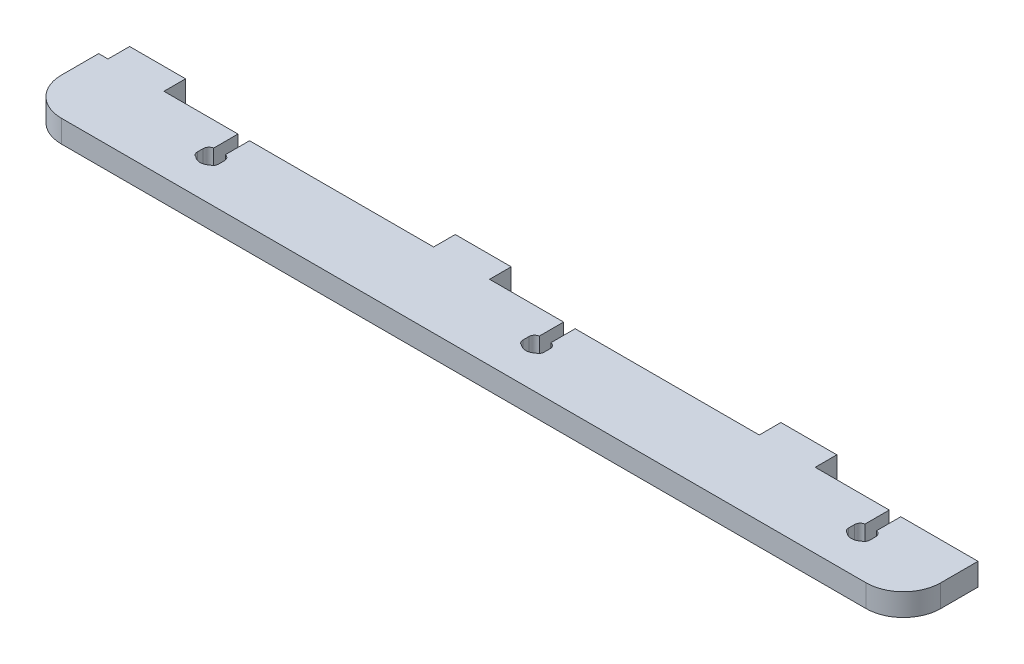
SolidWorks part; units mm, degrees
ref_plane "Alzado" through (0, 0, 0) normal (0, 0, 1) x (1, 0, 0)
ref_plane "Planta" through (0, 0, 0) normal (0, 1, 0) x (1, 0, 0)
ref_plane "Vista lateral" through (0, 0, 0) normal (1, 0, 0) x (0, 0, -1)
sketch "Croquis1" plane through (0, 0, 0) normal (0, 1, 0) x (1, 0, 0)
  line L0 (-32.5, 18.3594) -> (-32.5, 12.5594) construction
  line L1 (193.2444, 12.5594) -> (193.2444, 2.5594)
  line L2 (-42.5, 12.5594) -> (-42.5, 2.5594)
  line L3 (-32.5, -7.4406) -> (183.2444, -7.4406)
  line L7 (-40, 18.3594) -> (-25, 18.3594)
  line L8 (44.8, 12.5594) -> (47.3, 12.5594)
  line L9 (-5.15, 6.0592) -> (-5.15, 12.5594)
  line L10 (-2.05, 6.0592) -> (-2.05, 12.5594)
  line L11 (-0.7597, 4.5311) -> (-0.7597, 2.9811)
  line L12 (-1.4685, 1.6792) -> (-1.6378, 1.6792)
  line L13 (-5.7315, 1.6792) -> (-5.5622, 1.6792)
  line L14 (-6.4403, 4.5311) -> (-6.4403, 2.9811)
  line L15 (132.1, 12.5594) -> (134.6, 12.5594)
  line L16 (82.15, 6.0592) -> (82.15, 12.5594)
  line L17 (169.45, 6.0592) -> (169.45, 12.5594)
  line L18 (172.55, 6.0592) -> (172.55, 12.5594)
  line L19 (173.8403, 4.5311) -> (173.8403, 2.9811)
  line L20 (173.1315, 1.6792) -> (172.9622, 1.6792)
  line L21 (168.8685, 1.6792) -> (169.0378, 1.6792)
  line L22 (168.1597, 4.5311) -> (168.1597, 2.9811)
  line L23 (170.9, 12.5594) -> (170.9, 7.0553) construction
  line L24 (170.9, 12.5594) -> (170.9, 7.0553) construction
  line L25 (-2.05, 12.5594) -> (44.8, 12.5594)
  line L26 (47.3, 18.3594) -> (62.3, 18.3594)
  line L27 (134.6, 18.3594) -> (134.6, 12.5594)
  line L28 (54.8, 18.3594) -> (54.8, 12.5594) construction
  line L29 (35.6211, 12.5594) -> (44.8, 12.5594) construction
  line L30 (85.25, 6.0592) -> (85.25, 12.5594)
  line L31 (86.5403, 4.5311) -> (86.5403, 2.9811)
  line L32 (85.8315, 1.6792) -> (85.6622, 1.6792)
  line L33 (81.5685, 1.6792) -> (81.7378, 1.6792)
  line L34 (80.8597, 4.5311) -> (80.8597, 2.9811)
  line L35 (142.1, 18.3594) -> (142.1, 12.5594) construction
  line L36 (172.55, 12.5594) -> (193.2444, 12.5594)
  line L37 (85.25, 12.5594) -> (132.1, 12.5594)
  line L39 (134.6, 18.3594) -> (149.6, 18.3594)
  line L41 (152.1, 12.5594) -> (169.45, 12.5594)
  line L42 (64.8, 12.5594) -> (82.15, 12.5594)
  line L43 (54.8, 12.5594) -> (55.6211, 12.5594)
  line L44 (54.8, 12.5594) -> (55.6211, 12.5594) construction
  line L45 (-22.5, 12.5594) -> (-5.15, 12.5594)
  line L46 (47.3, 18.3594) -> (47.3, 12.5594)
  line L47 (-22.5, 12.5594) -> (-25, 12.5594)
  line L48 (-25, 18.3594) -> (-25, 12.5594)
  line L51 (-42.5, 12.5594) -> (-40, 12.5594)
  line L52 (-40, 18.3594) -> (-40, 12.5594)
  line L53 (64.8, 12.5594) -> (62.3, 12.5594)
  line L54 (62.3, 18.3594) -> (62.3, 12.5594)
  line L55 (152.1, 12.5594) -> (149.6, 12.5594)
  line L56 (149.6, 18.3594) -> (149.6, 12.5594)
  arc A0 (-0.7597, 4.5311) -> (-2.05, 6.0592) centre (-2.3097, 4.5311) ccw
  arc A1 (-1.4685, 1.6792) -> (-0.7597, 2.9811) centre (-2.3097, 2.9811) ccw
  arc A2 (-5.5622, 1.6792) -> (-1.6378, 1.6792) centre (-3.6, 3.6407) ccw
  arc A3 (-5.7315, 1.6792) -> (-6.4403, 2.9811) centre (-4.8903, 2.9811) cw
  arc A4 (-6.4403, 4.5311) -> (-5.15, 6.0592) centre (-4.8903, 4.5311) cw
  arc A5 (173.8403, 4.5311) -> (172.55, 6.0592) centre (172.2903, 4.5311) ccw
  arc A6 (173.1315, 1.6792) -> (173.8403, 2.9811) centre (172.2903, 2.9811) ccw
  arc A7 (169.0378, 1.6792) -> (172.9622, 1.6792) centre (171, 3.6407) ccw
  arc A8 (168.8685, 1.6792) -> (168.1597, 2.9811) centre (169.7097, 2.9811) cw
  arc A9 (168.1597, 4.5311) -> (169.45, 6.0592) centre (169.7097, 4.5311) cw
  arc A10 (86.5403, 4.5311) -> (85.25, 6.0592) centre (84.9903, 4.5311) ccw
  arc A11 (85.8315, 1.6792) -> (86.5403, 2.9811) centre (84.9903, 2.9811) ccw
  arc A12 (81.7378, 1.6792) -> (85.6622, 1.6792) centre (83.7, 3.6407) ccw
  arc A13 (81.5685, 1.6792) -> (80.8597, 2.9811) centre (82.4097, 2.9811) cw
  arc A14 (80.8597, 4.5311) -> (82.15, 6.0592) centre (82.4097, 4.5311) cw
  arc A15 (193.2444, 2.5594) -> (183.2444, -7.4406) centre (183.2444, 2.5594) cw
  arc A16 (-42.5, 2.5594) -> (-32.5, -7.4406) centre (-32.5, 2.5594) ccw
  point P9 (54.8, 12.5594)
  point P11 (45.6211, 12.5594)
  point P30 (-3.7, 12.5594)
  point P53 (83.6, 12.5594)
  point P55 (83.6, 12.5594)
  point P56 (142.1, 12.5594)
  point P57 (142.1, 12.5594)
  point P80 (170.9, 12.5594)
  point P86 (-42.5, -7.4406)
  dimension "D2" = 10
  dimension "D1" = 20
  dimension "D3" = 15
  dimension "D4" = 2.5
  dimension "D5" = 28.8
  dimension "D6" = 58.5
  dimension "D7" = 15
  dimension "D8" = 28.8
  dimension "D9" = 58.5
  dimension "D10" = 15
  dimension "D11" = 28.8
  dimension "D12" = 2.5
  dimension "D13" = 2.5
  dimension "D14" = 2.5
  dimension "D15" = 2.5
  dimension "D16" = 2.5
extrude "Saliente-Extruir1" add sketch "Croquis1" along normal blind 6
